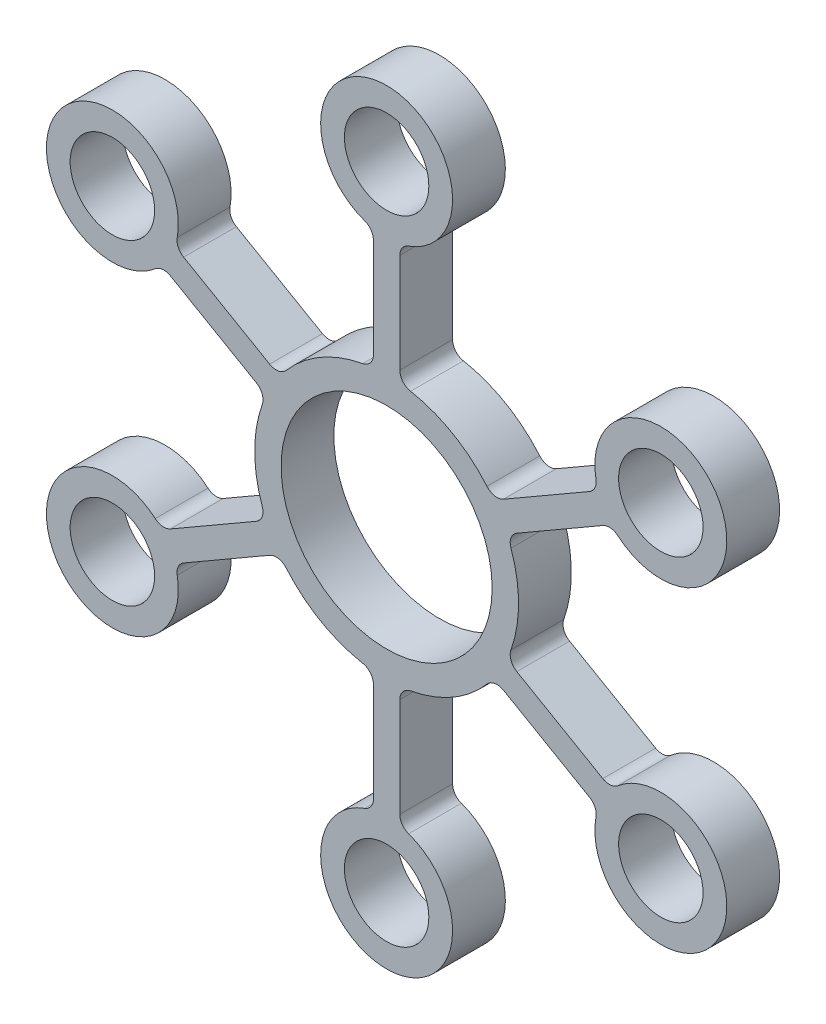
SolidWorks part; units mm, degrees
material "Thornel Mat VMA"
ref_plane "正面" through (0, 0, 0) normal (0, 0, 1) x (1, 0, 0)
ref_plane "平面" through (0, 0, 0) normal (0, 1, 0) x (1, 0, 0)
ref_plane "右側面" through (0, 0, 0) normal (1, 0, 0) x (0, 0, -1)
sketch "ｽｹｯﾁ1" plane through (0, 0, 0) normal (0, 0, 1) x (1, 0, 0)
  line L0 (0, 0) -> (0, 12) construction
  line L5 (4.0584, 2.9205) -> (8.021, 5.2083)
  line L6 (8.521, 4.3422) -> (4.5584, 2.0545)
  line L7 (0, 0) -> (10.3923, 6) construction
  line L8 (0, 0) -> (10.3923, -6) construction
  line L9 (0, 0) -> (0, -12) construction
  line L10 (0, 0) -> (-10.3923, -6) construction
  line L11 (0, 0) -> (-10.3923, 6) construction
  line L12 (0.5, 9.5505) -> (0.5, 4.9749)
  line L13 (-0.5, 4.9749) -> (-0.5, 9.5505)
  line L14 (4.5584, -2.0545) -> (8.521, -4.3422)
  line L15 (8.021, -5.2083) -> (4.0584, -2.9205)
  line L16 (0.5, -4.9749) -> (0.5, -9.5505)
  line L17 (-0.5, -9.5505) -> (-0.5, -4.9749)
  line L18 (-4.0584, -2.9205) -> (-8.021, -5.2083)
  line L19 (-8.521, -4.3422) -> (-4.5584, -2.0545)
  line L20 (-4.5584, 2.0545) -> (-8.521, 4.3422)
  line L21 (-8.021, 5.2083) -> (-4.0584, 2.9205)
  circle A0 centre (0, 12) radius 1.6
  circle A1 centre (10.3923, 6) radius 1.6
  circle A2 centre (10.3923, -6) radius 1.6
  circle A3 centre (0, -12) radius 1.6
  circle A4 centre (-10.3923, -6) radius 1.6
  circle A5 centre (-10.3923, 6) radius 1.6
  arc A6 (0.5, 9.5505) -> (-0.5, 9.5505) centre (0, 12) ccw
  circle A7 centre (0, 0) radius 4
  arc A8 (-0.5, 4.9749) -> (-4.0584, 2.9205) centre (0, 0) ccw
  arc A9 (8.521, 4.3422) -> (8.021, 5.2083) centre (10.3923, 6) ccw
  arc A10 (8.021, -5.2083) -> (8.521, -4.3422) centre (10.3923, -6) ccw
  arc A11 (-0.5, -9.5505) -> (0.5, -9.5505) centre (0, -12) ccw
  arc A12 (-8.521, -4.3422) -> (-8.021, -5.2083) centre (-10.3923, -6) ccw
  arc A13 (-8.021, 5.2083) -> (-8.521, 4.3422) centre (-10.3923, 6) ccw
  arc A14 (-4.5584, 2.0545) -> (-4.5584, -2.0545) centre (0, 0) ccw
  arc A15 (4.0584, 2.9205) -> (0.5, 4.9749) centre (0, 0) ccw
  arc A16 (4.5584, -2.0545) -> (4.5584, 2.0545) centre (0, 0) ccw
  arc A17 (0.5, -4.9749) -> (4.0584, -2.9205) centre (0, 0) ccw
  arc A18 (-4.0584, -2.9205) -> (-0.5, -4.9749) centre (0, 0) ccw
  point P0 (0, 0)
  point P3 (0, 0)
  point P21 (0, 0)
  point P25 (0.5, 7.2627)
  point P50 (0, 0)
  dimension "D3" = 3.2
  dimension "D5" = 5
  dimension "D1" = 8
  dimension "D7" = 10
  dimension "D2" = 12
  dimension "D6" = 1
  dimension "D8" = 6
  dimension "D4" = 6
extrude "ﾎﾞｽ - 押し出し1" add sketch "ｽｹｯﾁ1" along normal blind 2
fillet "ﾌｨﾚｯﾄ1" radius 0.5 24 edges at (8.021, 5.2083, 1) (8.521, 4.3422, 1) (4.5584, 2.0545, 1) (8.521, -4.3422, 1) (4.5584, -2.0545, 1) (8.021, -5.2083, 1) (4.0584, -2.9205, 1) (0.5, -4.9749, 1) (0.5, -9.5505, 1) (-0.5, -9.5505, 1) (-0.5, -4.9749, 1) (-8.021, -5.2083, 1) (-4.0584, -2.9205, 1) (-8.521, -4.3422, 1) (-4.5584, -2.0545, 1) (-4.5584, 2.0545, 1) (-8.521, 4.3422, 1) (-8.021, 5.2083, 1) (-4.0584, 2.9205, 1) (-0.5, 4.9749, 1) (-0.5, 9.5505, 1) (0.5, 9.5505, 1) (4.0584, 2.9205, 1) (0.5, 4.9749, 1)
